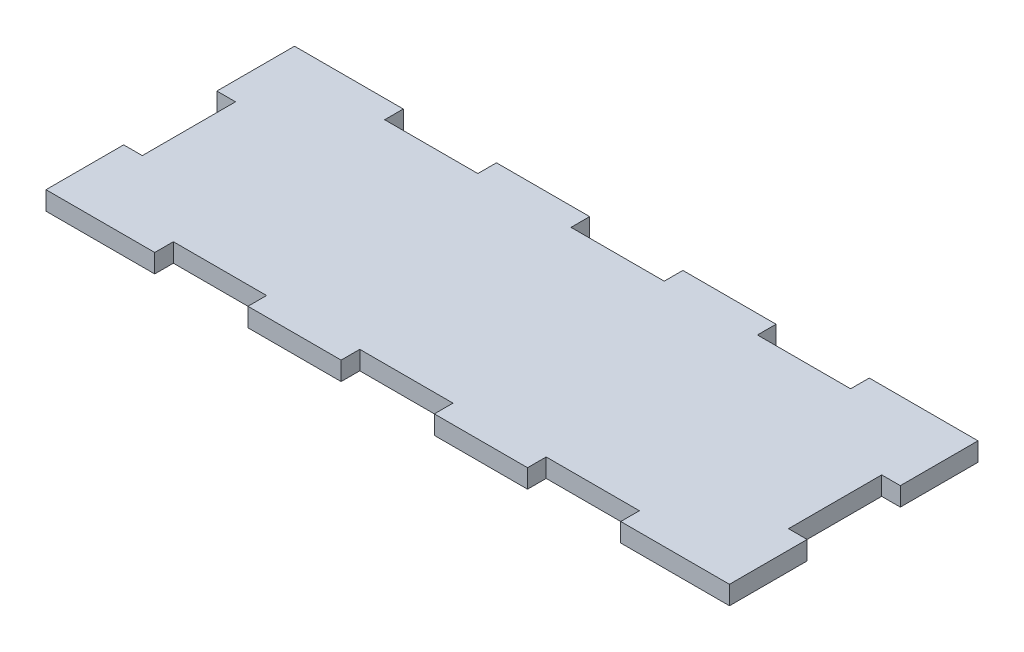
SolidWorks part; units mm, degrees
ref_plane "Alzado" through (0, 0, 0) normal (0, 0, 1) x (1, 0, 0)
ref_plane "Planta" through (0, 0, 0) normal (0, 1, 0) x (1, 0, 0)
ref_plane "Vista lateral" through (0, 0, 0) normal (1, 0, 0) x (0, 0, -1)
sketch "Croquis1" plane through (0, 0, 0) normal (0, 1, 0) x (1, 0, 0)
  line L0 (0, 0) -> (17.5, 0)
  line L1 (110, 0) -> (110, 12.5)
  line L2 (110, 40) -> (92.5, 40)
  line L3 (0, 40) -> (0, 27.5)
  line L5 (47.5, 3) -> (62.5, 3)
  line L6 (62.5, 3) -> (62.5, 0)
  line L7 (62.5, 0) -> (77.5, 0)
  line L8 (77.5, 0) -> (77.5, 3)
  line L9 (77.5, 3) -> (92.5, 3)
  line L10 (92.5, 3) -> (92.5, 0)
  line L11 (92.5, 0) -> (110, 0)
  line L12 (17.5, 3) -> (17.5, 0)
  line L13 (32.5, 3) -> (17.5, 3)
  line L14 (32.5, 0) -> (32.5, 3)
  line L15 (47.5, 3) -> (47.5, 0)
  line L16 (92.5, 0) -> (110, 0)
  line L17 (107, 12.5) -> (107, 27.5)
  line L18 (107, 27.5) -> (110, 27.5)
  line L19 (110, 27.5) -> (110, 40)
  line L20 (17.5, 40) -> (0, 40)
  line L21 (47.5, 40) -> (32.5, 40)
  line L22 (77.5, 40) -> (62.5, 40)
  line L23 (110, 27.5) -> (110, 40)
  line L24 (107, 12.5) -> (110, 12.5)
  line L25 (47.5, 37) -> (47.5, 40)
  line L26 (32.5, 40) -> (32.5, 37)
  line L27 (32.5, 37) -> (17.5, 37)
  line L28 (17.5, 37) -> (17.5, 40)
  line L29 (92.5, 37) -> (92.5, 40)
  line L30 (77.5, 37) -> (92.5, 37)
  line L31 (77.5, 40) -> (77.5, 37)
  line L32 (62.5, 37) -> (62.5, 40)
  line L33 (47.5, 37) -> (62.5, 37)
  line L34 (0, 12.5) -> (0, 0)
  line L35 (3, 12.5) -> (0, 12.5)
  line L36 (32.5, 0) -> (47.5, 0)
  line L37 (62.5, 0) -> (77.5, 0)
  line L40 (3, 27.5) -> (0, 27.5)
  line L41 (3, 12.5) -> (3, 27.5)
  dimension "D1" = 110
  dimension "D2" = 40
  dimension "D5" = 15
  dimension "D6" = 15
extrude "Saliente-Extruir2" add sketch "Croquis1" along normal blind 3 contours L41 L35 L34 L0 L12 L13 L14 L36 L15 L5 L6 L7 L8 L9 L10 L11 L1 L24 L17 L18 L19 L2 L29 L30 L31 L22 L32 L33 L25 L21 L26 L27 L28 L20 L3 L40
